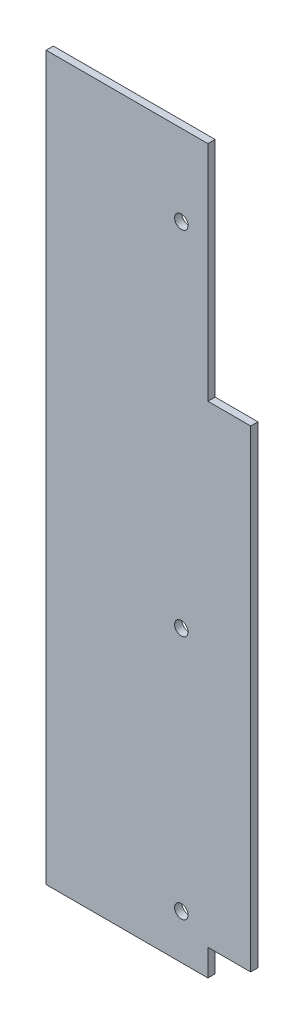
SolidWorks part; units mm, degrees
ref_plane "Front" through (0, 0, 0) normal (0, 0, 1) x (1, 0, 0)
ref_plane "Top" through (0, 0, 0) normal (0, 1, 0) x (1, 0, 0)
ref_plane "Right" through (0, 0, 0) normal (1, 0, 0) x (0, 0, -1)
sketch "Sketch1" plane through (0, 0, 0) normal (0, 0, 1) x (1, 0, 0)
  line L0 (0, 0) -> (0, 146.05)
  line L1 (0, 146.05) -> (35.56, 146.05)
  line L2 (35.56, 0) -> (35.56, 146.05)
  line L3 (0, 0) -> (35.56, 0)
  dimension "D4" = 146.05
  dimension "D2" = 35.56
extrude "Extrude1" add sketch "Sketch1" along normal blind 1.5875
sketch "Sketch3" plane through (35.56, 0, 0) normal (1, 0, 0) x (0, 0, -1)
  line L0 (-1.5875, 0) -> (-1.5875, 146.05) construction
  line L1 (-1.5875, 5.842) -> (0, 5.842)
  line L2 (-1.5875, 5.842) -> (-1.5875, 109.728)
  line L3 (-1.5875, 109.728) -> (0, 109.728)
  line L4 (0, 5.842) -> (0, 109.728)
  line L5 (0, 0) -> (0, 146.05) construction
  dimension "D1" = 103.886
  dimension "D2" = 5.842
extrude "Extrude2" add sketch "Sketch3" along normal blind 9.398
sketch "Sketch2" plane through (0, 0, 1.5875) normal (0, 0, 1) x (1, 0, 0)
  line L0 (0.635, 57.625) -> (10.635, 57.625)
  line L1 (0.635, 19.525) -> (10.635, 19.525)
  line L2 (0.635, 19.525) -> (0.635, 9.525)
  line L3 (0.635, 9.525) -> (10.635, 9.525)
  line L4 (10.635, 19.525) -> (10.635, 9.525)
  line L5 (10.635, 57.625) -> (10.635, 47.625)
  line L6 (0.635, 32.225) -> (10.635, 32.225)
  line L7 (10.635, 32.225) -> (10.635, 22.225)
  line L8 (0.635, 22.225) -> (10.635, 22.225)
  line L9 (0.635, 32.225) -> (0.635, 22.225)
  line L10 (0.635, 44.925) -> (10.635, 44.925)
  line L11 (10.635, 44.925) -> (10.635, 34.925)
  line L12 (0.635, 34.925) -> (10.635, 34.925)
  line L13 (0.635, 44.925) -> (0.635, 34.925)
  line L14 (0.635, 47.625) -> (10.635, 47.625)
  line L15 (0, 146.05) -> (0, 0) construction
  line L16 (0, 0) -> (35.56, 0) construction
  line L17 (0.635, 57.625) -> (0.635, 47.625)
  line L18 (0.635, 70.325) -> (10.635, 70.325)
  line L19 (10.635, 70.325) -> (10.635, 60.325)
  line L20 (0.635, 60.325) -> (10.635, 60.325)
  line L21 (0.635, 70.325) -> (0.635, 60.325)
  line L22 (0.635, 83.025) -> (10.635, 83.025)
  line L23 (10.635, 83.025) -> (10.635, 73.025)
  line L24 (0.635, 73.025) -> (10.635, 73.025)
  line L25 (0.635, 83.025) -> (0.635, 73.025)
  line L26 (0.635, 95.725) -> (10.635, 95.725)
  line L27 (10.635, 95.725) -> (10.635, 85.725)
  line L28 (0.635, 85.725) -> (10.635, 85.725)
  line L29 (0.635, 95.725) -> (0.635, 85.725)
  line L30 (0.635, 108.425) -> (10.635, 108.425)
  line L31 (10.635, 108.425) -> (10.635, 98.425)
  line L32 (0.635, 98.425) -> (10.635, 98.425)
  line L33 (0.635, 108.425) -> (0.635, 98.425)
  dimension "D1" = 9.525
  dimension "D2" = 10
  dimension "D3" = 10
  dimension "D4" = 12.7
  dimension "D5" = 12.7
  dimension "D6" = 0.635
sketch "Sketch4" plane through (44.958, 0, 0) normal (1, 0, 0) x (0, 0, -1)
  line L0 (0, 109.728) -> (-1.5875, 109.728) construction
  line L3 (0, 5.842) -> (0, 109.728) construction
  point P0 (-0.7937, 109.728)
  point P1 (0, 57.785)
  point P6 (-0.7937, 57.785)
sketch "Sketch5" plane through (0, 0, 1.5875) normal (0, 0, 1) x (1, 0, 0)
  line L0 (0, 146.05) -> (0, 0) construction
  line L1 (35.56, 146.05) -> (0, 146.05) construction
  point P0 (29.718, 9.779)
  point P1 (29.718, 63.627)
  point P2 (29.718, 140.97)
  dimension "D1" = 29.718
  dimension "D2" = 5.08
  dimension "D3" = 82.423
  dimension "D4" = 136.271
hole_wizard "#32 (0.116000) Diameter Hole1" positions "3DSketch1" profile "Sketch6" hole size "#32" standard "Ansi Inch"
sketch3d "3DSketch1"
  point P0 (29.718, 9.779, 1.5875)
  point P2 (29.718, 63.627, 1.5875)
  point P4 (29.718, 140.97, 1.5875)
sketch "Sketch6" plane through (29.718, 9.779, 1.5875) normal (1, 0, 0) x (0, -1, 0)
  line L0 (0, 0) -> (0, 26.2852)
  line L1 (0, 26.2852) -> (1.4732, 25.4)
  line L2 (1.4732, 25.4) -> (1.4732, 0)
  line L5 (1.4732, 0) -> (0, 0)
  line L10 (0, 26.2852) -> (-1.4732, 25.4) construction
  line L11 (0, -6.35) -> (0, 107.95) construction
  dimension "Hole Dia." = 2.9464
  dimension "Hole Depth" = 25.4
  dimension "Drill Angle" = 118
sketch "Sketch7" plane through (0, 146.05, 0) normal (0, 1, 0) x (-1, 0, 0)
  line L1 (0, 0) -> (-35.56, 0)
  line L2 (0, 0) -> (0, 1.5875)
  line L3 (0, 1.5875) -> (-35.56, 1.5875)
  line L4 (-35.56, 0) -> (-35.56, 1.5875)
extrude "Extrude3" add sketch "Sketch7" along normal blind 12.7
